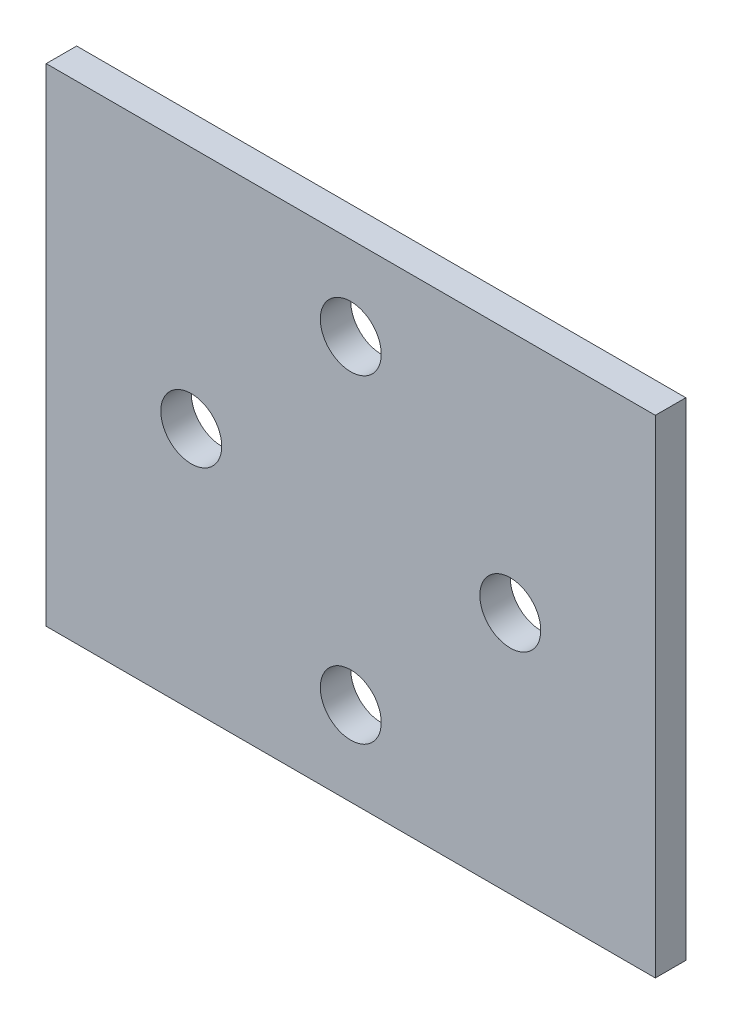
SolidWorks part; units mm, degrees
ref_plane "Front Plane" through (0, 0, 0) normal (0, 0, 1) x (1, 0, 0)
ref_plane "Top Plane" through (0, 0, 0) normal (0, 1, 0) x (1, 0, 0)
ref_plane "Right Plane" through (0, 0, 0) normal (1, 0, 0) x (0, 0, -1)
sketch "Sketch1" plane through (0, 0, 0) normal (0, 0, 1) x (1, 0, 0)
  line L0 (0, 0) -> (0, 40)
  line L1 (0, 0) -> (-26.1859, 0)
  line L3 (-50, 40) -> (50, 40)
  line L4 (-50, 40) -> (-50, -40)
  line L5 (-50, -40) -> (50, -40)
  line L6 (50, 40) -> (50, -40)
  circle A4 centre (-26.1859, 0) radius 5
  circle A5 centre (0, 26.1859) radius 5
  circle A6 centre (26.1859, 0) radius 5
  circle A7 centre (0, -26.1859) radius 5
  point P18 (0, 0)
  point P19 (0, 0)
  dimension "D2" = 4
  dimension "D1" = 40
  dimension "D3" = 100
  dimension "D4" = 80
extrude "Boss-Extrude3" add sketch "Sketch1" against normal blind 5
